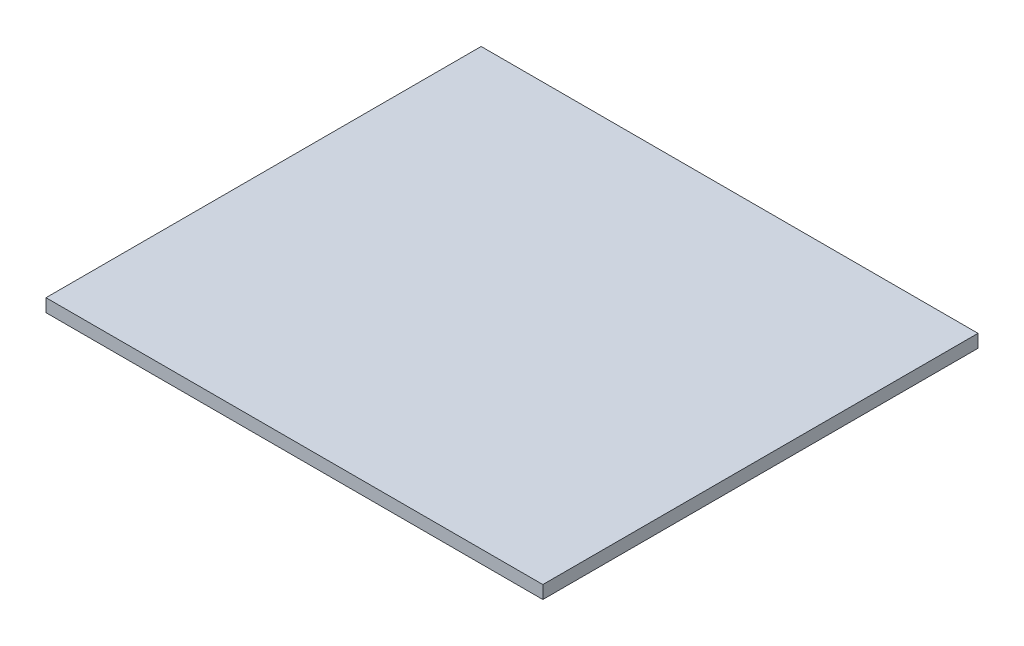
SolidWorks part; units mm, degrees
ref_plane "Front Plane" through (0, 0, 0) normal (0, 0, 1) x (1, 0, 0)
ref_plane "Top Plane" through (0, 0, 0) normal (0, 1, 0) x (1, 0, 0)
ref_plane "Right Plane" through (0, 0, 0) normal (1, 0, 0) x (0, 0, -1)
sketch "Sketch1" plane through (0, 0, 0) normal (0, 1, 0) x (1, 0, 0)
  line L1 (0, -96.38) -> (114.554, -96.38)
  line L2 (0, -96.38) -> (0, 3.95)
  line L3 (0, 3.95) -> (114.554, 3.95)
  line L4 (114.554, -96.38) -> (114.554, 3.95)
  dimension "D1" = 100.33
  dimension "D2" = 114.554
extrude "Boss-Extrude1" add sketch "Sketch1" along normal blind 2.9972
